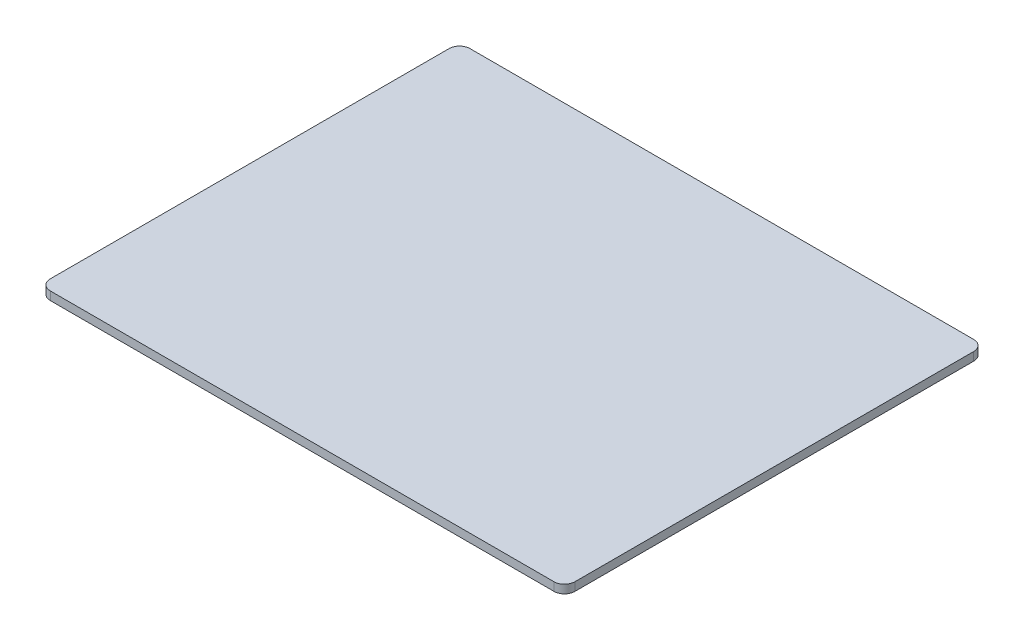
SolidWorks part; units mm, degrees
ref_plane "前视基准面" through (0, 0, 0) normal (0, 0, 1) x (1, 0, 0)
ref_plane "上视基准面" through (0, 0, 0) normal (0, 1, 0) x (1, 0, 0)
ref_plane "右视基准面" through (0, 0, 0) normal (1, 0, 0) x (0, 0, -1)
sketch "草图1" plane through (0, 0, 0) normal (0, 1, 0) x (1, 0, 0)
  line L1 (-50, -40) -> (50, -40)
  line L2 (-50, -40) -> (-50, 40)
  line L3 (-50, 40) -> (50, 40)
  line L4 (50, -40) -> (50, 40)
  line L5 (-50, -40) -> (50, 40) construction
  line L6 (-50, 40) -> (50, -40) construction
  point P0 (0, 0)
  dimension "D1" = 100
  dimension "D2" = 80
extrude "凸台-拉伸1" add sketch "草图1" along normal blind 1.6
fillet "圆角1" radius 2 4 edges at (50, 0.8, -40) (-50, 0.8, -40) (-50, 0.8, 40) (50, 0.8, 40)
